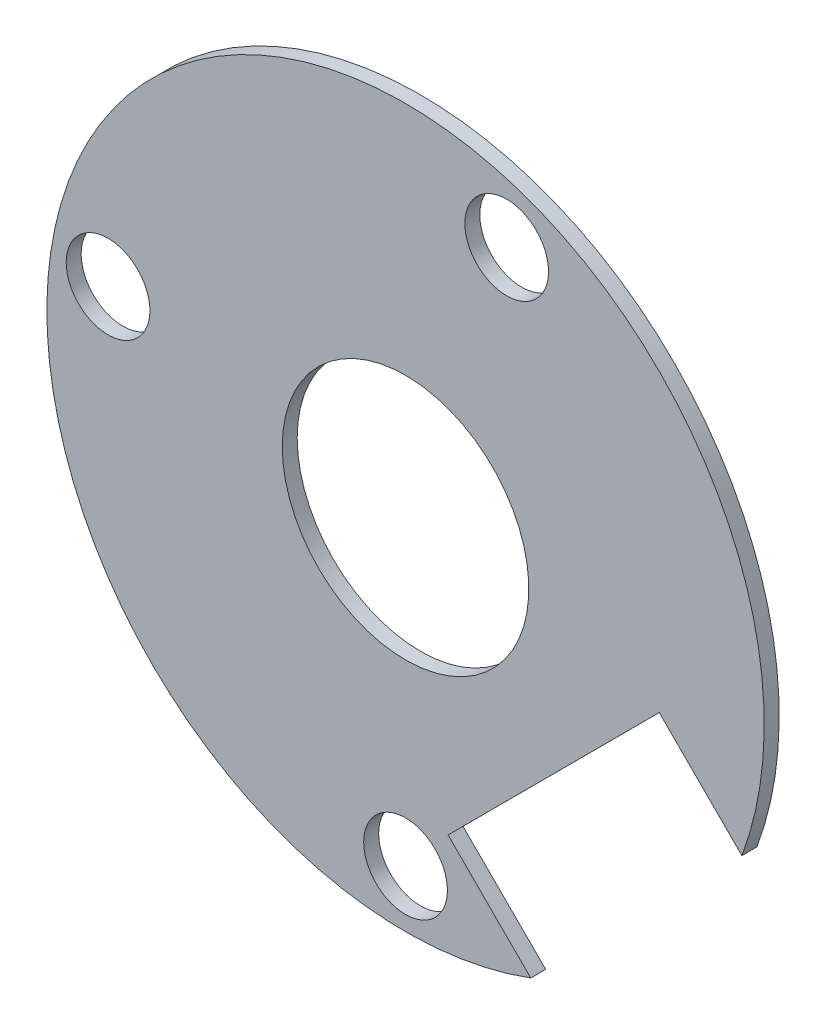
SolidWorks part; units mm, degrees
ref_plane "Front Plane" through (0, 0, 0) normal (0, 0, 1) x (1, 0, 0)
ref_plane "Top Plane" through (0, 0, 0) normal (0, 1, 0) x (1, 0, 0)
ref_plane "Right Plane" through (0, 0, 0) normal (1, 0, 0) x (0, 0, -1)
sketch "Sketch1" plane through (0, 0, 0) normal (1, 0, 0) x (0, 0, -1)
  line L0 (-76, 0) -> (124.5, 0)
  line L1 (-76, 0) -> (-76, 6)
  line L2 (-76, 6) -> (-52, 6)
  line L3 (-52, 6) -> (-52, 9)
  line L4 (-52, 9) -> (-50, 9)
  line L5 (-50, 9) -> (-50, 26)
  line L6 (-50, 26) -> (0, 26)
  line L7 (0, 26) -> (0, 25)
  line L8 (0, 25) -> (104, 25)
  line L10 (108, 8) -> (109, 8)
  line L12 (109, 8) -> (109, 4)
  line L13 (109, 4) -> (124.5, 4)
  line L14 (124.5, 4) -> (124.5, 0)
  line L15 (0, 0) -> (0, 25) construction
  line L16 (104, 25) -> (104, 24)
  line L17 (104, 24) -> (108, 24)
  line L18 (108, 24) -> (108, 8)
  dimension "D1" = 4
  dimension "D2" = 25
  dimension "D3" = 8
  dimension "D4" = 24
  dimension "D5" = 26
  dimension "D6" = 9
  dimension "D7" = 6
  dimension "D8" = 15.5
  dimension "D9" = 1
  dimension "D10" = 4
  dimension "D11" = 104
  dimension "D12" = 50
  dimension "D13" = 2
  dimension "D14" = 24
revolve "Revolve1" add sketch "Sketch1" angle 360 about L0
sketch "Sketch3" plane through (0, 0, -108) normal (0, 0, 1) x (1, 0, 0)
  line L0 (0, 0) -> (-17.1467, 2.9579) construction
  line L1 (-17.1467, 2.9579) -> (-19.906, 3.4339) construction
  line L2 (-19.906, 3.4339) -> (-22.6652, 3.9099) construction
  line L3 (-22.6652, 3.9099) -> (-23.6507, 4.0799) construction
  line L4 (0, 0) -> (5.8297, 16.3943) construction
  line L5 (5.8297, 16.3943) -> (6.7679, 19.0325) construction
  line L6 (6.7679, 19.0325) -> (7.706, 21.6707) construction
  line L7 (7.706, 21.6707) -> (8.041, 22.6129) construction
  line L8 (0, 0) -> (0, -17.4) construction
  line L9 (0, -17.4) -> (0, -20.2) construction
  line L10 (0, -20.2) -> (0, -23) construction
  line L11 (0, -23) -> (0, -24) construction
  line L12 (6.7679, 19.0325) -> (4.3508, 17.619) construction
  line L13 (4.3508, 17.619) -> (-17.4889, 4.8474) construction
  line L14 (-17.4889, 4.8474) -> (-19.906, 3.4339) construction
  line L15 (0, -20.2) -> (-1.8038, -18.0584) construction
  line L16 (-1.8038, -18.0584) -> (-18.1022, 1.2923) construction
  line L17 (-18.1022, 1.2923) -> (-19.906, 3.4339) construction
  circle A0 centre (6.7679, 19.0325) radius 2.8
  circle A1 centre (-19.906, 3.4339) radius 2.8
  circle A2 centre (0, -20.2) radius 2.8
  circle A3 centre (0, 0) radius 24 construction
  point P9 (0, 0)
  point P12 (0, 0)
  point P13 (0, -26.1873)
  point P18 (0, 0)
  point P20 (0, 0)
  point P26 (0, 0)
  point P27 (0, 0)
  point P30 (0, 0)
  point P31 (-23.7401, 3.8248)
  point P32 (8.8615, 19.8205)
  point P33 (0, 0)
  point P34 (-22.7963, 4.9038)
  point P35 (0, 0)
  dimension "D1" = 5.6
  dimension "D2" = 1
  dimension "D3" = 25.3
  dimension "D4" = 25.3
extrude "Cut-Extrude2" cut sketch "Sketch3" along normal blind 3.25
sketch "Sketch4" plane through (0, 0, -108) normal (0, 0, -1) x (-1, 0, 0)
  line L0 (-22.5064, -8.3343) -> (-16.9733, -2.8119)
  line L1 (-16.9733, -2.8119) -> (-2.8449, -16.9678)
  line L2 (-2.8449, -16.9678) -> (-8.3781, -22.4902)
  line L3 (-8.3781, -22.4902) -> (-11.3385, -25.4448)
  line L4 (-11.3385, -25.4448) -> (-25.4668, -11.2889)
  line L5 (-25.4668, -11.2889) -> (-22.5064, -8.3343)
  line L6 (-9.9091, -9.8899) -> (16.9871, 16.954) construction
  line L7 (-9.9091, -9.8899) -> (0, -20.2) construction
  circle A0 centre (0, 0) radius 24 construction
  circle A1 centre (0, 0) radius 26 construction
  circle A2 centre (0, 0) radius 24 construction
  dimension "D1" = 38
  dimension "D2" = 20
  dimension "D3" = 14.3
extrude "Cut-Extrude3" cut sketch "Sketch4" against normal blind 2
sketch "Sketch5" plane through (0, 0, -108) normal (0, 0, -1) x (-1, 0, 0)
  circle A0 centre (0, 0) radius 8.25
  circle A1 centre (0, 0) radius 8 construction
  dimension "D1" = 0.25
extrude "Cut-Extrude4" cut sketch "Sketch5" against normal through all both and the other way through all
sketch "Sketch6" plane through (0, 0, 0) normal (0, 1, 0) x (1, 0, 0)
  line L0 (24, 108) -> (-24, 108) construction
  line L1 (37.6623, 107) -> (-42.7166, 107)
  line L2 (37.6623, 107) -> (37.6623, -80.0073)
  line L3 (37.6623, -80.0073) -> (-42.7166, -80.0073)
  line L4 (-42.7166, 107) -> (-42.7166, -80.0073)
  dimension "D1" = 1
extrude "Cut-Extrude5" cut sketch "Sketch6" against normal through all both and the other way through all
